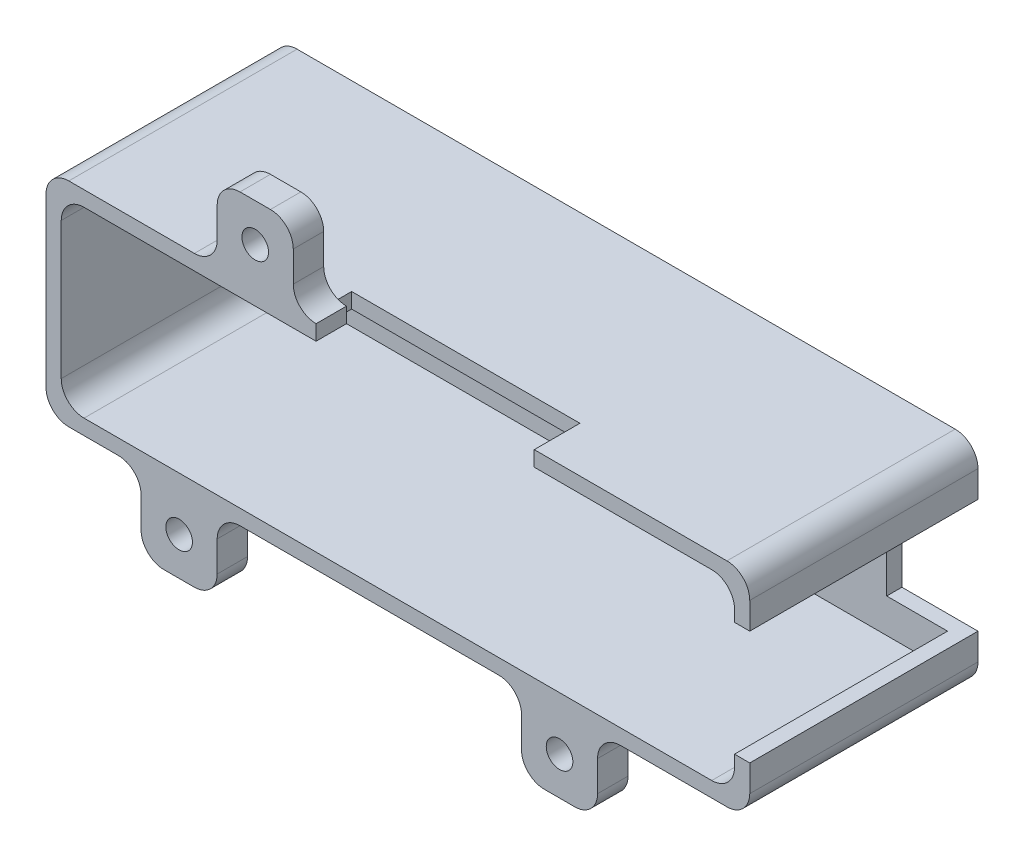
SolidWorks part; units mm, degrees
ref_plane "Front Plane" through (0, 0, 0) normal (0, 0, 1) x (1, 0, 0)
ref_plane "Top Plane" through (0, 0, 0) normal (0, 1, 0) x (1, 0, 0)
ref_plane "Right Plane" through (0, 0, 0) normal (1, 0, 0) x (0, 0, -1)
sketch "Sketch1" plane through (0, 0, 0) normal (0, 1, 0) x (1, 0, 0)
  line L1 (-52.3875, -19.05) -> (52.3875, -19.05)
  line L2 (-52.3875, -19.05) -> (-52.3875, 19.05)
  line L3 (-52.3875, 19.05) -> (52.3875, 19.05)
  line L4 (52.3875, -19.05) -> (52.3875, 19.05)
  line L5 (-52.3875, -19.05) -> (52.3875, 19.05) construction
  line L6 (-52.3875, 19.05) -> (52.3875, -19.05) construction
  line L7 (52.3875, -19.05) -> (65.0875, -19.05)
  line L8 (52.3875, -19.05) -> (52.3875, 19.05)
  line L9 (52.3875, 19.05) -> (65.0875, 19.05)
  line L10 (65.0875, -19.05) -> (65.0875, 19.05)
  point P0 (0, 0)
  dimension "D1" = 38.1
  dimension "D2" = 104.775
  dimension "D3" = 12.7
extrude "Boss-Extrude1" add sketch "Sketch1" along normal blind 35.56 contours L7 L10 L9 L4 | L1 L4 L3 L2
sketch "Sketch2" plane through (65.0875, 0, 0) normal (-1, 0, 0) x (0, 0, 1)
  line L0 (0, 0) -> (0, 33.02) construction
  line L1 (-19.05, 35.56) -> (-19.05, 0) construction
  line L3 (19.05, 17.78) -> (-19.05, 17.78) construction
  line L6 (15.24, 32.0675) -> (15.24, 3.4925)
  line L11 (19.05, 3.4925) -> (-19.05, 3.4925)
  line L12 (19.05, 3.4925) -> (19.05, 32.0675)
  line L13 (19.05, 32.0675) -> (-19.05, 32.0675)
  line L14 (-19.05, 3.4925) -> (-19.05, 32.0675)
  line L15 (19.05, 3.4925) -> (-19.05, 32.0675) construction
  line L16 (19.05, 32.0675) -> (-19.05, 3.4925) construction
  line L17 (-15.24, 32.0675) -> (-15.24, 3.4925)
  point P9 (-19.05, 17.78)
  point P12 (0, 16.51)
  point P13 (0, 17.78)
  line M32 (19.05, 35.56) -> (19.05, 0)
  dimension "D1" = 28.575
  dimension "D2" = 3.81
  dimension "D3" = 3.81
extrude "Cut-Extrude1" [suppressed] cut sketch "Sketch2" along normal blind 111.76 contours L17 L13 L6 L11 | L13 L11 L6 M32
sketch "Sketch11" plane through (0, 0, 19.05) normal (0, 0, 1) x (1, 0, 0)
  line L0 (-52.3875, 35.56) -> (-52.3875, 0) construction
  line L1 (-49.8475, 2.54) -> (62.5475, 2.54)
  line L2 (-49.8475, 2.54) -> (-49.8475, 33.02)
  line L3 (-49.8475, 33.02) -> (62.5475, 33.02)
  line L4 (62.5475, 2.54) -> (62.5475, 33.02)
  line L5 (-52.3875, 35.56) -> (65.0875, 35.56) construction
  point P6 (-52.3875, 17.78)
  point P7 (-49.8475, 17.78)
  point P10 (6.35, 35.56)
  point P11 (6.35, 33.02)
  dimension "D1" = 30.48
  dimension "D2" = 2.54
  dimension "D3" = 2.54
extrude "Cut-Extrude9" cut sketch "Sketch11" against normal offset from surface (35.56 mm away) 2.54 up to face at (6.35, 17.78, -19.05)
sketch "Sketch3" plane through (0, 35.56, 0) normal (0, 1, 0) x (1, 0, 0)
  line L2 (65.0875, -19.05) -> (65.0875, 19.05) construction
  line L4 (-52.3875, 19.05) -> (65.0875, 19.05) construction
  circle A0 centre (60.0075, 0) radius 2.54
  dimension "D1" = 19.05
  dimension "D2" = 5.08
extrude "Cut-Extrude2" [suppressed] cut sketch "Sketch3" against normal blind 41.402
sketch "Sketch5" plane through (0, 0, 0) normal (0, -1, 0) x (1, 0, 0)
  line L3 (39.6875, 13.97) -> (26.9875, 13.97)
  line L4 (26.9875, 19.05) -> (26.9875, 13.97)
  line L6 (-23.8125, 19.05) -> (-36.5125, 19.05)
  line L7 (-23.8125, 19.05) -> (-23.8125, 13.97)
  line L8 (-23.8125, 13.97) -> (-36.5125, 13.97)
  line L9 (-36.5125, 19.05) -> (-36.5125, 13.97)
  line L10 (39.6875, 13.97) -> (39.6875, 19.05)
  line L11 (-52.3875, 19.05) -> (65.0875, 19.05) construction
  line L12 (65.0875, 19.05) -> (65.0875, -19.05) construction
  line L13 (39.6875, 19.05) -> (26.9875, 19.05)
  dimension "D1" = 25.4
  dimension "D2" = 5.08
  dimension "D3" = 12.7
  dimension "D4" = 5.08
  dimension "D5" = 50.8
  dimension "D6" = 12.7
extrude "Boss-Extrude2" add sketch "Sketch5" along normal blind 12.7 contours L6 L9 L8 L7 | L10 L13 L4 L3
sketch "Sketch7" plane through (0, 35.56, 0) normal (0, 1, 0) x (1, 0, 0)
  line L0 (-23.8125, -19.05) -> (-36.5125, -19.05) construction
  line L1 (-36.5125, -19.05) -> (-36.5125, -13.97) construction
  line L2 (-36.5125, -13.97) -> (-23.8125, -13.97) construction
  line L3 (-23.8125, -13.97) -> (-23.8125, -19.05) construction
  line L4 (26.9875, -13.97) -> (39.6875, -13.97) construction
  line L5 (39.6875, -13.97) -> (39.6875, -19.05) construction
  line L6 (39.6875, -19.05) -> (26.9875, -19.05) construction
  line L7 (26.9875, -19.05) -> (26.9875, -13.97) construction
  line L8 (-23.8125, -19.05) -> (-36.5125, -19.05)
  line L9 (-36.5125, -19.05) -> (-36.5125, -13.97)
  line L10 (-36.5125, -13.97) -> (-23.8125, -13.97)
  line L11 (-23.8125, -13.97) -> (-23.8125, -19.05)
  line L12 (26.9875, -13.97) -> (39.6875, -13.97)
  line L13 (39.6875, -13.97) -> (39.6875, -19.05)
  line L14 (39.6875, -19.05) -> (26.9875, -19.05)
  line L15 (26.9875, -19.05) -> (26.9875, -13.97)
  line L16 (-52.3875, -19.05) -> (65.0875, -19.05) construction
  line L17 (-23.8125, -19.05) -> (-11.1125, -19.05)
  line L18 (-23.8125, -19.05) -> (-23.8125, -13.97)
  line L19 (-23.8125, -13.97) -> (-11.1125, -13.97)
  line L20 (-11.1125, -19.05) -> (-11.1125, -13.97)
  line M7 (-52.3875, -19.05) -> (65.0875, -19.05)
  dimension "D1" = 12.7
  dimension "D2" = 5.08
  dimension "D3" = 0
extrude "Boss-Extrude3" add sketch "Sketch7" along normal blind 12.7 contours L20 L19 L18 M7
sketch "Sketch8" plane through (0, 0, 13.97) normal (0, 0, -1) x (-1, 0, 0)
  line L0 (17.4625, 41.91) -> (17.4625, 48.26) construction
  line L1 (-33.3375, -6.35) -> (-26.9875, -6.35) construction
  line L2 (-26.9875, -12.7) -> (-26.9875, 0) construction
  line L3 (-33.3375, -6.35) -> (-33.3375, -12.7) construction
  line L4 (30.1625, -6.35) -> (23.8125, -6.35) construction
  line L5 (23.8125, -12.7) -> (23.8125, 0) construction
  line L6 (30.1625, -6.35) -> (30.1625, -12.7) construction
  line L7 (17.4625, 41.91) -> (-9.6475, 41.91) construction
  line L13 (23.8125, 48.26) -> (11.1125, 48.26) construction
  line L14 (23.8125, 48.26) -> (23.8125, 35.56) construction
  circle A0 centre (-33.3375, -6.35) radius 6.35 construction
  circle A1 centre (30.1625, -6.35) radius 6.35 construction
  circle A2 centre (-33.3375, -6.35) radius 2.2225
  circle A3 centre (30.1625, -6.35) radius 2.2225
  circle A6 centre (17.4625, 41.91) radius 3.2975 construction
  circle A7 centre (17.4625, 41.91) radius 2.2225
  point P32 (17.4625, 48.26)
  point P34 (23.8125, 41.91)
  dimension "D1" = 6.35
  dimension "D3" = 6.35
  dimension "D4" = 4.445
  dimension "D5" = 4.445
  dimension "D6" = 4.445
  dimension "D2" = 6.35
extrude "Cut-Extrude6" cut sketch "Sketch8" against normal through all
fillet "Fillet1" radius 3.81 20 edges at (-23.8125, -12.7, 16.51) (-36.5125, -12.7, 16.51) (26.9875, -12.7, 16.51) (39.6875, -12.7, 16.51) (-23.8125, 48.26, 16.51) (-11.1125, 48.26, 16.51) (-23.8125, 35.56, 16.51) (-11.1125, 35.56, 16.51) (-36.5125, 0, 16.51) (-23.8125, 0, 16.51) (26.9875, 0, 16.51) (39.6875, 0, 16.51) (-52.3875, 0, 0) (-52.3875, 35.56, 0) (62.5475, 2.54, 1.27) (62.5475, 33.02, 1.27) (-49.8475, 2.54, 1.27) (-49.8475, 33.02, 1.27) (65.0875, 0, 0) (65.0875, 35.56, 0)
sketch "Sketch9" plane through (0, 0, -19.05) normal (0, 0, -1) x (-1, 0, 0)
  line L0 (-65.0875, 27.305) -> (-52.3875, 27.305)
  line L3 (-52.3875, 27.305) -> (-52.3875, 8.255)
  line L6 (-52.3875, 8.255) -> (-65.0875, 8.255)
  line L13 (-65.0875, 31.75) -> (-65.0875, 3.81) construction
  line L15 (-65.0875, 8.255) -> (-65.0875, 27.305)
  point P10 (-65.0875, 17.78)
  point P15 (-65.0875, 17.78)
  dimension "D3" = 19.05
  dimension "D1" = 12.7
extrude "Cut-Extrude7" cut sketch "Sketch9" against normal through all
sketch "Sketch10" plane through (0, 35.56, 0) normal (0, 1, 0) x (1, 0, 0)
  line L2 (-23.8125, -19.05) -> (65.0875, -19.05) construction
  line L3 (3.7125, -19.05) -> (-8.9875, -19.05)
  line L4 (3.7125, -19.05) -> (3.7125, -11.43)
  line L5 (3.7125, -11.43) -> (-8.9875, -11.43)
  line L6 (-8.9875, -19.05) -> (-8.9875, -11.43)
  line L8 (3.7125, -19.05) -> (29.1125, -19.05)
  line L9 (3.7125, -19.05) -> (3.7125, -11.43)
  line L10 (3.7125, -11.43) -> (29.1125, -11.43)
  line L11 (29.1125, -19.05) -> (29.1125, -11.43)
  dimension "D1" = 7.62
  dimension "D2" = 12.7
  dimension "D4" = 25.4
extrude "Cut-Extrude8" cut sketch "Sketch10" against normal blind 8.89
equation "\"D3@Sketch11\"=\"D2@Sketch11\""
